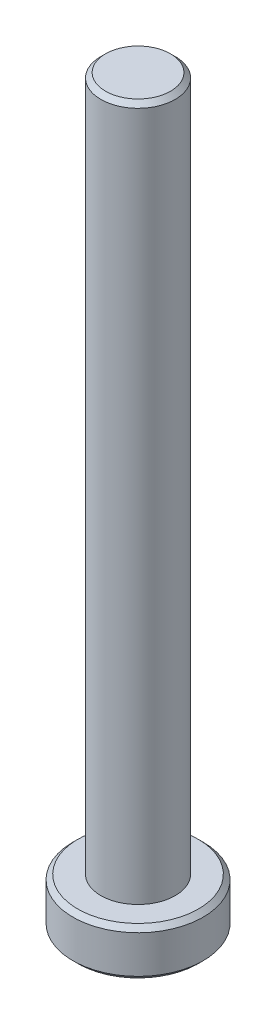
SolidWorks part; units mm, degrees
material "Plain Carbon Steel"
ref_plane "Front Plane" through (0, 0, 0) normal (0, 0, 1) x (1, 0, 0)
ref_plane "Top Plane" through (0, 0, 0) normal (0, 1, 0) x (1, 0, 0)
ref_plane "Right Plane" through (0, 0, 0) normal (1, 0, 0) x (0, 0, -1)
sketch "Sketch1" plane through (0, 0, 0) normal (0, 1, 0) x (1, 0, 0)
  circle A0 centre (0, 0) radius 2
  dimension "D1" = 4
extrude "Boss-Extrude1" add sketch "Sketch1" along normal blind 37.338 contours A0
sketch "Sketch2" plane through (0, 0, 0) normal (0, -1, 0) x (1, 0, 0)
  circle A0 centre (0, 0) radius 3.5
  dimension "D1" = 7
extrude "Boss-Extrude2" add sketch "Sketch2" along normal blind 2.54 contours A0
chamfer "Chamfer1" distance 0.254 angle 45 1 edges at (0, -2.54, -3.5)
chamfer "Chamfer2" distance 0.254 angle 45 1 edges at (0, 37.338, 2)
chamfer "Chamfer3" distance 0.254 angle 45 1 edges at (0, 0, -3.5)
